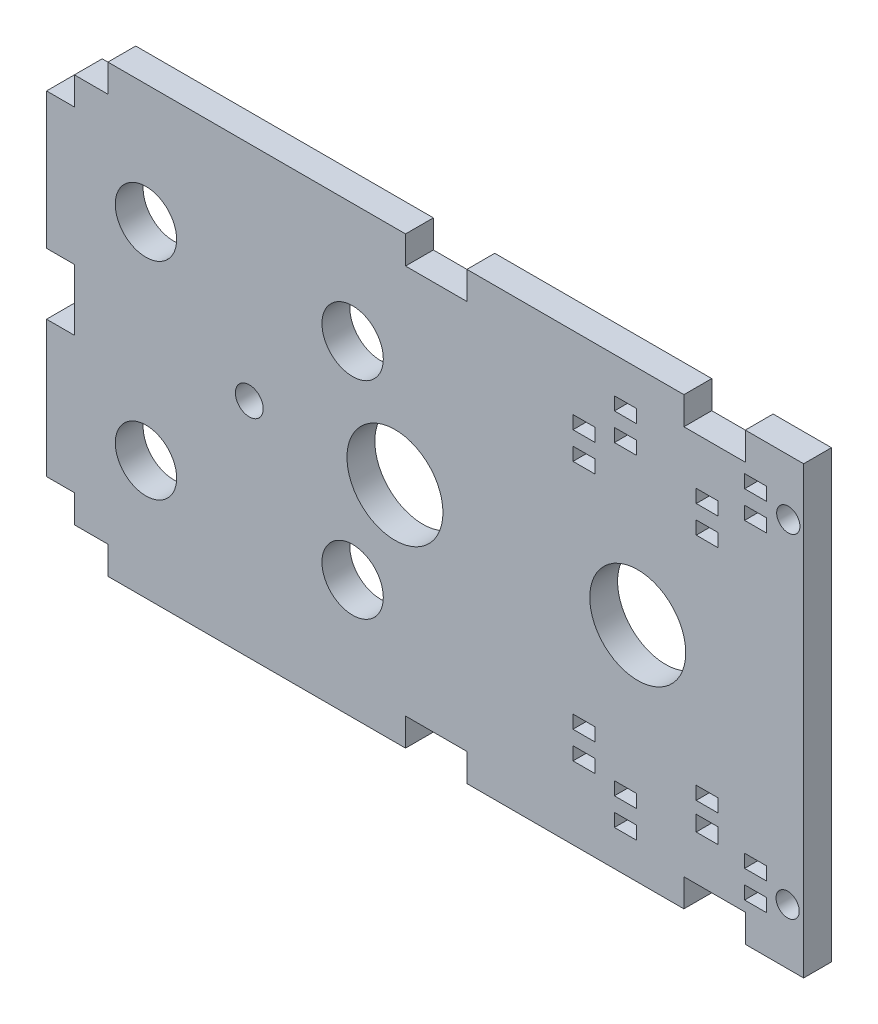
SolidWorks part; units mm, degrees
ref_plane "Front Plane" through (0, 0, 0) normal (0, 0, 1) x (1, 0, 0)
ref_plane "Top Plane" through (0, 0, 0) normal (0, 1, 0) x (1, 0, 0)
ref_plane "Right Plane" through (0, 0, 0) normal (1, 0, 0) x (0, 0, -1)
sketch "Sketch2" plane through (0, 0, 0) normal (0, 0, 1) x (1, 0, 0)
  line L1 (-88.9, -50.8) -> (88.9, -50.8)
  line L2 (-88.9, -50.8) -> (-88.9, 50.8)
  line L3 (-88.9, 50.8) -> (88.9, 50.8)
  line L4 (88.9, -50.8) -> (88.9, 50.8)
  line L5 (-88.9, -50.8) -> (88.9, 50.8) construction
  line L6 (-88.9, 50.8) -> (88.9, -50.8) construction
  point P0 (0, 0)
  dimension "D1" = 101.6
  dimension "D2" = 177.8
extrude "Boss-Extrude3" add sketch "Sketch2" along normal blind 6.35
sketch "Sketch3" plane through (0, 0, 6.35) normal (0, 0, 1) x (1, 0, 0)
  line L0 (-88.9, 0) -> (0, 0) construction
  line L1 (-88.9, 50.8) -> (-88.9, -50.8) construction
  line L2 (0, 0) -> (88.9, 0) construction
  line L3 (88.9, -50.8) -> (88.9, 50.8) construction
  line L4 (0, 50.8) -> (0, -50.8) construction
  line L5 (88.9, 50.8) -> (-88.9, 50.8) construction
  line L6 (-88.9, -50.8) -> (88.9, -50.8) construction
  line L7 (-9.4121, 0) -> (-42.6438, 0) construction
  line L8 (45.9739, 0) -> (-9.4121, 0) construction
  line L21 (-66.2169, -23.5732) -> (-19.0706, -23.5732)
  line L22 (-66.2169, -23.5732) -> (-66.2169, 23.5732)
  line L23 (-66.2169, 23.5732) -> (-19.0706, 23.5732)
  line L24 (-19.0706, -23.5732) -> (-19.0706, 23.5732)
  line L25 (-66.2169, -23.5732) -> (-19.0706, 23.5732) construction
  line L26 (-66.2169, 23.5732) -> (-19.0706, -23.5732) construction
  line L29 (26.7151, -50.8) -> (26.7151, 50.8) construction
  line L30 (-66.2169, 23.5732) -> (-66.2169, 30.5732) construction
  circle A1 centre (-9.4121, 0) radius 10.95
  circle A2 centre (-42.6438, 0) radius 3.175
  circle A3 centre (-66.2169, 23.5732) radius 7
  circle A4 centre (-19.0706, 23.5732) radius 7
  circle A5 centre (-66.2169, -23.5732) radius 7
  circle A6 centre (-19.0706, -23.5732) radius 7
  circle A7 centre (45.9739, 0) radius 10.95
  dimension "D1" = 6.35
  dimension "D2" = 14
  dimension "D3" = 14
  dimension "D4" = 14
  dimension "D8" = 14
  dimension "D9" = 21.9
  dimension "D10" = 21.9
  dimension "D5" = 55.386
  dimension "D6" = 33.2317
  dimension "D7" = 46.2563
extrude "Cut-Extrude1" cut sketch "Sketch3" against normal through all contours A3 | A6 | A5 | A1 | A7 | A2 | A4
sketch "Sketch7" plane through (0, 0, 6.35) normal (0, 0, 1) x (1, 0, 0)
  line L0 (-19.0706, 30.5732) -> (-19.0706, 50.8) construction
  line L1 (88.9, 50.8) -> (-88.9, 50.8) construction
  line L2 (-61.405, 18.4893) -> (-88.9, 18.4893) construction
  line L3 (-88.9, 50.8) -> (-88.9, -50.8) construction
  line L4 (-88.9, -7) -> (-88.9, 7)
  line L5 (-88.9, 50.8) -> (-74.9, 50.8)
  line L6 (-88.9, 50.8) -> (-88.9, 44.45)
  line L7 (-74.9, 44.45) -> (-82.55, 44.45)
  line L8 (-74.9, 50.8) -> (-74.9, 44.45)
  line L9 (-88.9, -50.8) -> (-74.9, -50.8)
  line L10 (-88.9, -50.8) -> (-88.9, -44.45)
  line L11 (-74.9, -44.45) -> (-82.55, -44.45)
  line L12 (-74.9, -50.8) -> (-74.9, -44.45)
  line L13 (-88.9, -7) -> (-82.55, -7)
  line L14 (-88.9, 7) -> (-82.55, 7)
  line L15 (-82.55, -7) -> (-82.55, 7)
  line L16 (88.9, -50.8) -> (88.9, 50.8) construction
  line L17 (7, 44.45) -> (-7, 44.45)
  line L18 (7, 44.45) -> (7, 50.8)
  line L19 (7, 50.8) -> (-7, 50.8)
  line L20 (-7, 44.45) -> (-7, 50.8)
  line L21 (70.509, 50.8) -> (70.509, 44.45)
  line L22 (88.9, -50.8) -> (83.82, -50.8)
  line L23 (7, -50.8) -> (56.509, -50.8)
  line L24 (56.509, -50.8) -> (70.509, -50.8)
  line L25 (56.509, -50.8) -> (56.509, -44.45)
  line L26 (56.509, -44.45) -> (70.509, -44.45)
  line L27 (70.509, -50.8) -> (70.509, -44.45)
  line L28 (56.509, 44.45) -> (70.509, 44.45)
  line L29 (56.509, 50.8) -> (56.509, 44.45)
  line L30 (56.509, 50.8) -> (70.509, 50.8)
  line L31 (7, 50.8) -> (56.509, 50.8)
  line L32 (83.82, 50.8) -> (88.9, 50.8)
  line L33 (-88.9, -50.8) -> (88.9, -50.8) construction
  line L34 (7, -50.8) -> (-7, -50.8)
  line L35 (7, -50.8) -> (7, -44.45)
  line L36 (-7, -50.8) -> (-7, -44.45)
  line L37 (7, -44.45) -> (-7, -44.45)
  line L38 (-88.9, -7) -> (-88.9, -44.45) construction
  line L39 (83.82, 50.8) -> (83.82, -50.8)
  line L40 (-88.9, -7) -> (-82.55, 7) construction
  line L41 (88.9, -50.8) -> (88.9, 50.8)
  line L43 (0, 0) -> (-88.9, 0) construction
  line L44 (-82.55, -7) -> (-88.9, 7) construction
  line L46 (-88.9, 0) -> (88.9, 0) construction
  line L47 (0, 50.8) -> (0, -50.8) construction
  line L48 (0, 50.8) -> (0, 44.45) construction
  line L49 (0, -44.45) -> (0, -50.8) construction
  line L50 (-82.55, 44.45) -> (-82.55, 38.1)
  line L51 (-82.55, 38.1) -> (-88.9, 38.1)
  line L52 (-88.9, 44.45) -> (-88.9, 38.1)
  line L54 (-82.55, -44.45) -> (-82.55, -38.1)
  line L55 (-82.55, -38.1) -> (-88.9, -38.1)
  line L56 (-88.9, -44.45) -> (-88.9, -38.1)
  circle A0 centre (-19.0706, 23.5732) radius 7 construction
  circle A2 centre (-66.2169, 23.5732) radius 7 construction
  line M8 (88.9, -50.8) -> (88.9, 50.8)
  line M9 (88.9, 50.8) -> (-88.9, 50.8)
  line M10 (-88.9, 50.8) -> (-88.9, -50.8)
  line M11 (-88.9, -50.8) -> (88.9, -50.8)
  dimension "D1" = 20.2268
  dimension "D2" = 27.495
  dimension "D5" = 6.35
  dimension "D6" = 6.35
  dimension "D7" = 6.35
  dimension "D8" = 49.509
  dimension "D9" = 18.391
extrude "Cut-Extrude2" cut sketch "Sketch7" against normal through all contours L27 L26 L25 M11 | L29 L28 L21 M9 | L20 L17 L18 M9 | L35 L37 L36 M11 | L54 L55 L12 L11 M10 M11 | L13 L15 L14 M10 | L51 L50 L7 L8 M9 M10 | L39 M9 M11 M8
sketch "Sketch8" plane through (0, 0, 0) normal (0, 0, -1) x (-1, 0, 0)
  line L0 (-76.2102, -50.8) -> (-83.82, -50.8)
  line L1 (-83.82, 50.8) -> (-83.82, -50.8) construction
  line L2 (-64.309, -24.965) -> (-64.309, -27.965)
  line L3 (-64.309, -34.215) -> (-59.309, -34.215)
  line L4 (-59.309, -27.965) -> (-59.309, -24.965)
  line L5 (-59.309, -34.215) -> (-45.6437, -34.215) construction
  line L6 (-59.309, -34.215) -> (-59.3218, -30.6949)
  line L7 (-59.309, -24.965) -> (-64.309, -24.965)
  line L8 (-64.309, -27.965) -> (-59.309, -27.965)
  line L9 (-59.309, -27.965) -> (-59.2672, -30.5011)
  line L10 (-64.309, -34.215) -> (-64.3218, -30.6949)
  line L11 (-64.309, -27.965) -> (-64.3218, -30.6949)
  line L12 (-27.5234, 50.8) -> (-27.5234, -50.8)
  line L13 (-56.509, 50.8) -> (-7, 50.8) construction
  line L14 (-7, -50.8) -> (-56.509, -50.8) construction
  line L15 (-31.2018, 29.59) -> (-27.5234, 29.59)
  line L16 (-36.189, -24.965) -> (-36.189, -27.965)
  line L17 (-36.189, -34.215) -> (-31.189, -34.215)
  line L18 (-31.189, -24.965) -> (-31.189, -27.965)
  line L19 (-31.189, -34.215) -> (-31.189, -31.215)
  line L20 (-31.189, -24.965) -> (-36.189, -24.965)
  line L21 (-36.189, -27.965) -> (-31.189, -27.965)
  line L22 (-36.189, -31.215) -> (-31.189, -31.215)
  line L23 (-36.189, -27.965) -> (-36.189, -29.59)
  line L24 (-36.189, -34.215) -> (-36.189, -31.215)
  line L25 (-36.189, -29.59) -> (-36.189, -31.215)
  line L26 (-31.189, -27.965) -> (-31.189, -31.215) construction
  line L27 (-31.189, -31.215) -> (-31.1344, -31.0212) construction
  line L28 (-76.8206, 50.7114) -> (-76.8194, -0.0461) construction
  line L29 (-31.2018, 31.215) -> (-31.1472, 31.0212) construction
  line L30 (-31.2018, 27.965) -> (-31.2018, 31.215) construction
  line L31 (-59.3218, 29.59) -> (-36.2018, 29.59) construction
  line L32 (-59.3218, 30.6949) -> (-59.2672, 30.5011) construction
  line L33 (-59.3218, 27.4449) -> (-59.3218, 30.6949) construction
  line L34 (-36.2018, 29.59) -> (-36.2018, 31.215)
  line L35 (-36.2018, 34.215) -> (-36.2018, 31.215)
  line L36 (-36.2018, 27.965) -> (-36.2018, 29.59)
  line L37 (-36.2018, 31.215) -> (-31.2018, 31.215)
  line L38 (-36.2018, 27.965) -> (-31.2018, 27.965)
  line L39 (-31.2018, 24.965) -> (-36.2018, 24.965)
  line L40 (-31.2018, 34.215) -> (-31.2018, 31.215)
  line L41 (-31.2018, 24.965) -> (-31.2018, 27.965)
  line L42 (-36.2018, 34.215) -> (-31.2018, 34.215)
  line L43 (-36.2018, 24.965) -> (-36.2018, 27.965)
  line L44 (-64.3218, 29.0699) -> (-64.3218, 30.6949)
  line L45 (-64.3218, 30.6949) -> (-64.3218, 33.6949)
  line L46 (-64.3218, 27.4449) -> (-64.3218, 29.0699)
  line L47 (-64.3218, 30.6949) -> (-59.3218, 30.6949)
  line L48 (-64.3218, 27.4449) -> (-59.3218, 27.4449)
  line L49 (-59.3218, 24.4449) -> (-64.3218, 24.4449)
  line L50 (-59.3218, 33.6949) -> (-59.3218, 30.6949)
  line L51 (-59.3218, 24.4449) -> (-59.3218, 27.4449)
  line L52 (-64.3218, 33.6949) -> (-59.3218, 33.6949)
  line L53 (-64.3218, 24.4449) -> (-64.3218, 27.4449)
  line L54 (-76.8194, -0.0461) -> (-76.2102, -50.8)
  line L55 (-76.8206, 50.7114) -> (-83.82, 25.3326) construction
  line L56 (-70.509, 44.45) -> (-83.82, 44.45)
  line L57 (-83.82, 25.3326) -> (-76.82, 25.3326)
  line L58 (-76.82, 25.3326) -> (-83.82, 50.8) construction
  line L59 (-56.509, 44.45) -> (-70.509, 44.45) construction
  line L60 (-83.82, -50.8) -> (-76.2102, -50.8) construction
  line L61 (-70.509, 50.8) -> (-70.509, 44.45) construction
  line L62 (-76.5148, -25.4231) -> (-83.82, -50.8) construction
  line L63 (-76.82, 25.3326) -> (-83.82, 25.3326) construction
  line L64 (-83.82, -50.8) -> (-76.2102, -50.8) construction
  line L65 (-83.82, -50.8) -> (-76.2102, -50.8) construction
  line L66 (-76.5148, -25.4231) -> (-83.82, -25.4231) construction
  line L67 (-83.82, -25.4231) -> (-76.2102, -50.8) construction
  line L68 (-76.8206, 50.7114) -> (-83.82, 50.8) construction
  line L69 (-70.3504, 37.5019) -> (-75.3504, 37.5019) construction
  line L70 (-70.3504, 39.1269) -> (-70.2958, 38.9331) construction
  line L71 (-70.3504, 35.8769) -> (-70.3504, 39.1269) construction
  line L72 (-75.3504, 37.5019) -> (-75.3504, 39.1269)
  line L73 (-75.3504, 42.1269) -> (-75.3504, 39.1269)
  line L74 (-75.3504, 35.8769) -> (-75.3504, 37.5019)
  line L75 (-75.3504, 39.1269) -> (-70.3504, 39.1269)
  line L76 (-75.3504, 35.8769) -> (-70.3504, 35.8769)
  line L77 (-70.3504, 32.8769) -> (-75.3504, 32.8769)
  line L78 (-70.3504, 42.1269) -> (-70.3504, 39.1269)
  line L79 (-70.3504, 32.8769) -> (-70.3504, 35.8769)
  line L80 (-75.3504, 42.1269) -> (-70.3504, 42.1269)
  line L81 (-75.3504, 32.8769) -> (-75.3504, 35.8769)
  line L82 (-70.3504, 33.6949) -> (-64.3218, 33.6949)
  line L83 (-36.2018, 34.215) -> (-40.6437, 34.215)
  line L85 (-40.6437, -36.397) -> (-40.6437, -39.647) construction
  line L86 (-40.6437, -39.647) -> (-40.5892, -39.4532) construction
  line L87 (-40.6437, -38.022) -> (-45.6437, -38.022) construction
  line L88 (-70.3504, -35.8769) -> (-70.3504, -39.1269) construction
  line L89 (-70.3504, -39.1269) -> (-70.2958, -38.9331) construction
  line L90 (-70.3504, -37.5019) -> (-75.3504, -37.5019) construction
  line L91 (-76.8206, -50.7114) -> (-83.82, -50.8) construction
  line L92 (-76.8206, -50.7114) -> (-83.82, -25.3326) construction
  line L94 (-59.3218, -30.6949) -> (-59.2672, -30.5011) construction
  line L95 (-40.6437, 38.022) -> (-45.6437, 38.022) construction
  line L96 (-40.6437, 39.647) -> (-40.5892, 39.4532) construction
  line L97 (-40.6437, 36.397) -> (-40.6437, 39.647) construction
  line L98 (-45.6437, 38.022) -> (-45.6437, 39.647)
  line L99 (-45.6437, 42.647) -> (-45.6437, 39.647)
  line L100 (-45.6437, 36.397) -> (-45.6437, 38.022)
  line L101 (-45.6437, 39.647) -> (-40.6437, 39.647)
  line L102 (-45.6437, 36.397) -> (-40.6437, 36.397)
  line L103 (-40.6437, 33.397) -> (-45.6437, 33.397)
  line L104 (-40.6437, 42.647) -> (-40.6437, 39.647)
  line L105 (-40.6437, 33.397) -> (-40.6437, 36.397)
  line L106 (-45.6437, 42.647) -> (-40.6437, 42.647)
  line L107 (-45.6437, 33.397) -> (-45.6437, 36.397)
  line L109 (-31.2018, -27.965) -> (-31.2018, -31.215) construction
  line L110 (-31.2018, -31.215) -> (-31.1472, -31.0212) construction
  line L111 (-76.8206, -50.7114) -> (-76.8194, 0.0461) construction
  line L112 (-45.6437, -33.397) -> (-45.6437, -36.397)
  line L113 (-45.6437, -42.647) -> (-40.6437, -42.647)
  line L114 (-40.6437, -33.397) -> (-40.6437, -36.397)
  line L115 (-40.6437, -42.647) -> (-40.6437, -39.647)
  line L116 (-40.6437, -33.397) -> (-45.6437, -33.397)
  line L117 (-45.6437, -36.397) -> (-40.6437, -36.397)
  line L118 (-45.6437, -39.647) -> (-40.6437, -39.647)
  line L119 (-45.6437, -36.397) -> (-45.6437, -38.022)
  line L120 (-45.6437, -42.647) -> (-45.6437, -39.647)
  line L121 (-45.6437, -38.022) -> (-45.6437, -39.647)
  line L122 (-36.2018, -34.215) -> (-40.6437, -34.215)
  line L123 (-70.3504, -33.6949) -> (-64.3218, -33.6949)
  line L124 (-75.3504, -32.8769) -> (-75.3504, -35.8769)
  line L125 (-75.3504, -42.1269) -> (-70.3504, -42.1269)
  line L126 (-70.3504, -32.8769) -> (-70.3504, -35.8769)
  line L127 (-70.3504, -42.1269) -> (-70.3504, -39.1269)
  line L128 (-70.3504, -32.8769) -> (-75.3504, -32.8769)
  line L129 (-75.3504, -35.8769) -> (-70.3504, -35.8769)
  line L130 (-75.3504, -39.1269) -> (-70.3504, -39.1269)
  line L131 (-75.3504, -35.8769) -> (-75.3504, -37.5019)
  line L132 (-75.3504, -42.1269) -> (-75.3504, -39.1269)
  line L133 (-75.3504, -37.5019) -> (-75.3504, -39.1269)
  line L134 (-70.509, -44.45) -> (-83.82, -44.45)
  line L141 (-64.3218, -30.6949) -> (-59.3218, -30.6949)
  line L145 (-36.2018, -24.965) -> (-36.2018, -27.965)
  line L146 (-36.2018, -34.215) -> (-31.2018, -34.215)
  line L147 (-31.2018, -24.965) -> (-31.2018, -27.965)
  line L148 (-31.2018, -34.215) -> (-31.2018, -31.215)
  line L149 (-31.2018, -24.965) -> (-36.2018, -24.965)
  line L150 (-36.2018, -27.965) -> (-31.2018, -27.965)
  line L151 (-36.2018, -31.215) -> (-31.2018, -31.215)
  line L152 (-36.2018, -27.965) -> (-36.2018, -29.59)
  line L153 (-36.2018, -34.215) -> (-36.2018, -31.215)
  line L154 (-36.2018, -29.59) -> (-36.2018, -31.215)
  circle A0 centre (-80.3203, 38.022) radius 2.65
  circle A1 centre (-80.1674, -38.1115) radius 2.65
  dimension "D1" = 5.3
  dimension "D3" = 6.428
  dimension "D2" = 23.12
  dimension "D4" = 0.818
  dimension "D5" = 6.0285
  dimension "D6" = 4.4419
  dimension "D7" = 4.4419
  dimension "D8" = 6.0285
extrude "Cut-Extrude3" cut sketch "Sketch8" against normal through all contours L24 L17 L19 L22 | A0 | L80 L73 L75 L78 | L81 L77 L79 L76 | L106 L99 L101 L104 | L112 L117 L114 L116 | L132 L125 L127 L130 | L124 L129 L126 L128 | L52 L45 L47 L50
